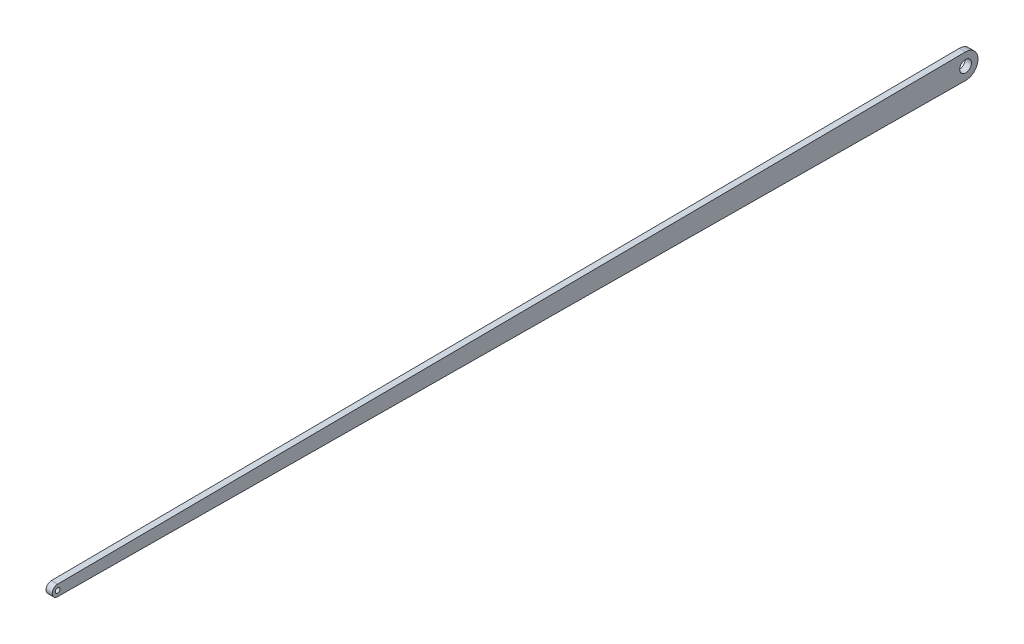
SolidWorks part; units mm, degrees
ref_plane "Front Plane" through (0, 0, 0) normal (0, 0, 1) x (1, 0, 0)
ref_plane "Top Plane" through (0, 0, 0) normal (0, 1, 0) x (1, 0, 0)
ref_plane "Right Plane" through (0, 0, 0) normal (1, 0, 0) x (0, 0, -1)
sketch "Sketch1" plane through (0, 0, 0) normal (1, 0, 0) x (0, 0, -1)
  line L0 (0, 0) -> (-7300, 0) construction
  line L1 (-7300, -43.75) -> (0, -100)
  line L2 (0, 100) -> (-7300, 43.75)
  arc A0 (0, -100) -> (0, 100) centre (0, 0) ccw
  arc A1 (-7300, 43.75) -> (-7300, -43.75) centre (-7300, 0) ccw
  circle A2 centre (0, 0) radius 46.875
  circle A3 centre (-7300, 0) radius 18.75
  dimension "D2" = 100
  dimension "D3" = 93.75
  dimension "D4" = 43.75
  dimension "D5" = 37.5
  dimension "D1" = 7300
extrude "Boss-Extrude1" add sketch "Sketch1" along normal blind 50
